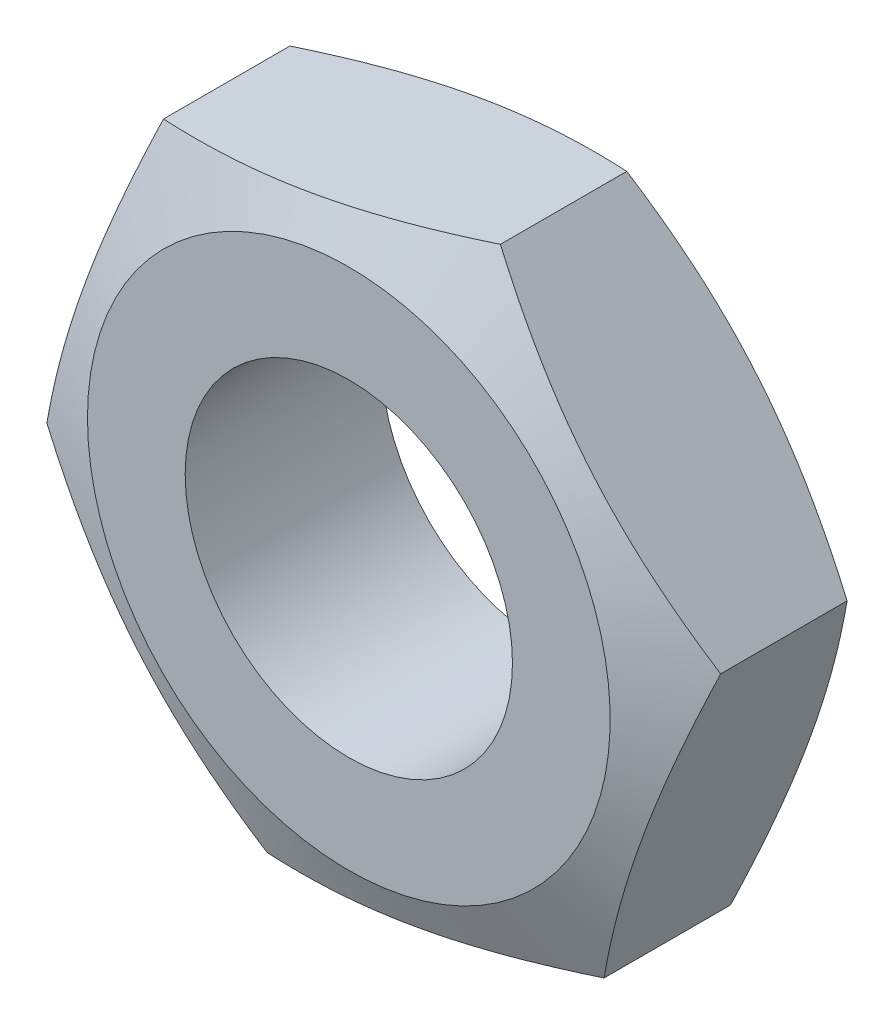
SolidWorks part; units mm, degrees
ref_plane "前视基准面" through (0, 0, 0) normal (0, 0, 1) x (1, 0, 0)
ref_plane "上视基准面" through (0, 0, 0) normal (0, 1, 0) x (1, 0, 0)
ref_plane "右视基准面" through (0, 0, 0) normal (1, 0, 0) x (0, 0, -1)
sketch "草图1" plane through (0, 0, 0) normal (0, 0, 1) x (1, 0, 0)
  line L1 (-0.8906, -2.4574) -> (1.6829, -2)
  line L2 (1.6829, -2) -> (2.5735, 0.4574)
  line L3 (2.5735, 0.4574) -> (0.8906, 2.4574)
  line L4 (0.8906, 2.4574) -> (-1.6829, 2)
  line L5 (-1.6829, 2) -> (-2.5735, -0.4574)
  line L6 (-2.5735, -0.4574) -> (-0.8906, -2.4574)
  circle A0 centre (0, 0) radius 2.2636 construction
  circle A1 centre (0, 0) radius 1.25
  dimension "D1" = 2.5
  dimension "D2" = 2
extrude "凸台-拉伸1" add sketch "草图1" along normal blind 1.5
sketch "草图2" plane through (0.3961, -2.2287, 0) normal (0.175, -0.9846, 0) x (0.9846, 0.175, 0)
  line L0 (0, 1.5) -> (0, 1.0994) construction
  line L3 (1.3069, 1.5) -> (2.6138, 1.5) construction
  line L5 (2.6138, 1.5) -> (2.6138, 0) construction
  line L6 (2.6138, 1.2498) -> (1.9604, 1.5)
  line L7 (2.6138, 1.5) -> (2.6138, 1.2498)
  line L8 (2.6138, 1.5) -> (1.9604, 1.5)
sketch "草图3" plane through (0, 0, 0) normal (0, 1, 0) x (1, 0, 0)
  line L0 (0.3961, -200001.5) -> (0.3961, 199998.9006) construction
  line L4 (0.3961, -200001.5) -> (0.3961, 199998.9006)
  line L8 (0, 0) -> (0, -0.7255)
  line L11 (2.5735, -1.5) -> (0.8906, -1.5) construction
  line L12 (1.9964, -1.5) -> (2.5735, -1.5)
  line L14 (1.9964, -1.5) -> (2.7044, -1.1936)
  line L15 (2.7044, -1.1936) -> (2.7044, -1.5)
  line L16 (2.9696, -1.5) -> (2.3262, -1.5) construction
  line L17 (2.7044, -1.5) -> (2.5735, -1.5)
revolve "切除-旋转1" cut sketch "草图3" angle 360 about L8
ref_plane "基准面1" through (0, 0, 0.75) normal (0, 0, 1) x (1, 0, 0)
mirror "镜向1" about plane through (0, 0, 0.75) normal (0, 0, 1) of "切除-旋转1"
